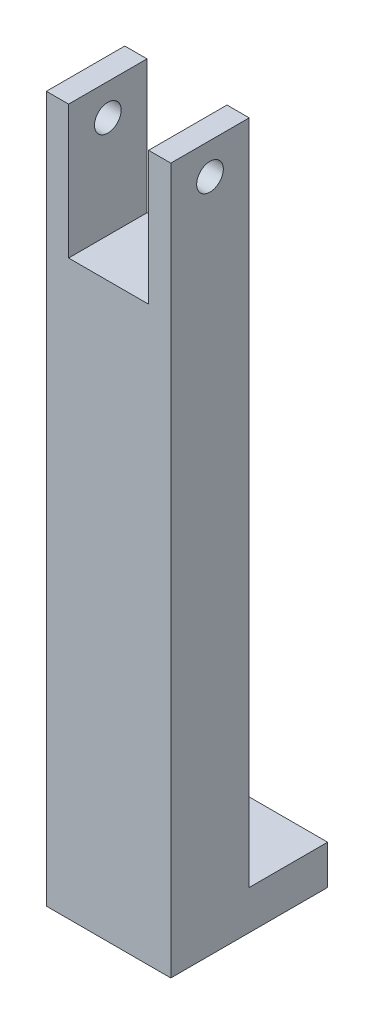
SolidWorks part; units mm, degrees
ref_plane "Ön Düzlem" through (0, 0, 0) normal (0, 0, 1) x (1, 0, 0)
ref_plane "Üst Düzlem" through (0, 0, 0) normal (0, 1, 0) x (1, 0, 0)
ref_plane "Sağ Düzlem" through (0, 0, 0) normal (1, 0, 0) x (0, 0, -1)
sketch "Çizim2" plane through (0, 0, 0) normal (0, 0, 1) x (1, 0, 0)
  line L0 (0, 0) -> (0, 79.3333)
  line L1 (0, 85) -> (2.8333, 85)
  line L2 (15.8667, 79.3333) -> (15.8667, 0)
  line L3 (0, 0) -> (15.8667, 0)
  line L4 (0, 79.3333) -> (0, 85)
  line L5 (2.8333, 85) -> (2.8333, 68)
  line L6 (15.8667, 85) -> (15.8667, 79.3333)
  line L7 (2.8333, 68) -> (13.0333, 68)
  line L8 (13.0333, 68) -> (13.0333, 85)
  line L9 (13.0333, 85) -> (15.8667, 85)
  dimension "D1" = 17
extrude "Yükseklik-Ekstrüzyon1" add sketch "Çizim2" along normal blind 10
sketch "Çizim3" plane through (0, 0, 0) normal (0, 0, -1) x (-1, 0, 0)
  line L0 (-15.8667, 0) -> (-15.8667, -5)
  line L1 (-15.8667, -5) -> (0, -5)
  line L2 (0, -5) -> (0, 0)
  line L3 (0, 0) -> (-15.8667, 0)
extrude "Yükseklik-Ekstrüzyon2" add sketch "Çizim3" along normal blind 10 and the other way up to surface (10 mm away) other way up to face at (7.9333, 59.5, 10)
sketch "Çizim5" plane through (15.8667, 0, 0) normal (1, 0, 0) x (0, 0, -1)
  line L0 (-10, 85) -> (0, 85) construction
  circle A0 centre (-5, 81) radius 1.7
  dimension "D1" = 4
extrude "Kes-Ekstrüzyon1" cut sketch "Çizim5" against normal blind 36
sketch "Çizim9" plane through (0, 0, 0) normal (0, 1, 0) x (1, 0, 0)
  circle A0 centre (7.9333, 5) radius 1.7
extrude "Kes-Ekstrüzyon2" cut sketch "Çizim9" against normal blind 36
